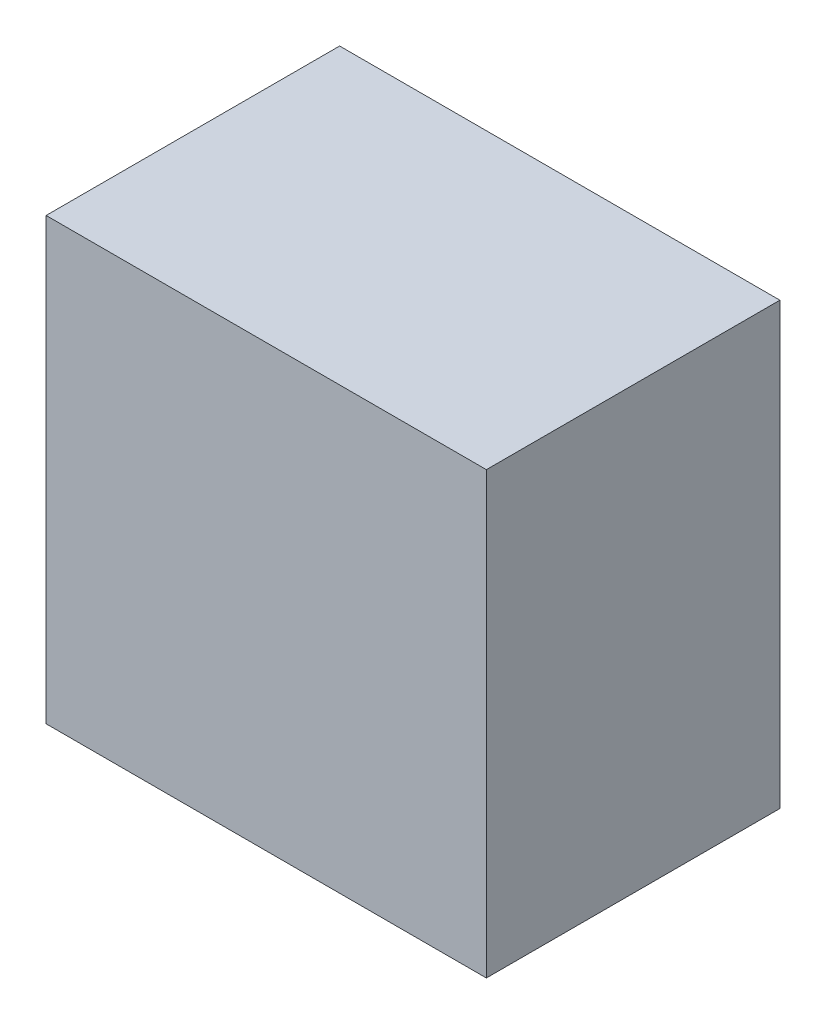
SolidWorks part; units mm, degrees
ref_plane "Front Plane" through (0, 0, 0) normal (0, 0, 1) x (1, 0, 0)
ref_plane "Top Plane" through (0, 0, 0) normal (0, 1, 0) x (1, 0, 0)
ref_plane "Right Plane" through (0, 0, 0) normal (1, 0, 0) x (0, 0, -1)
sketch "Sketch2" plane through (0, 0, 0) normal (0, 0, 1) x (1, 0, 0)
  line L1 (-27, 27) -> (27, 27)
  line L2 (-27, 27) -> (-27, -27)
  line L3 (-27, -27) -> (27, -27)
  line L4 (27, 27) -> (27, -27)
  line L5 (-27, 27) -> (27, -27) construction
  line L6 (-27, -27) -> (27, 27) construction
  point P0 (0, 0)
  dimension "D1" = 54
  dimension "D2" = 54
extrude "Boss-Extrude1" add sketch "Sketch2" along normal mid plane 36
